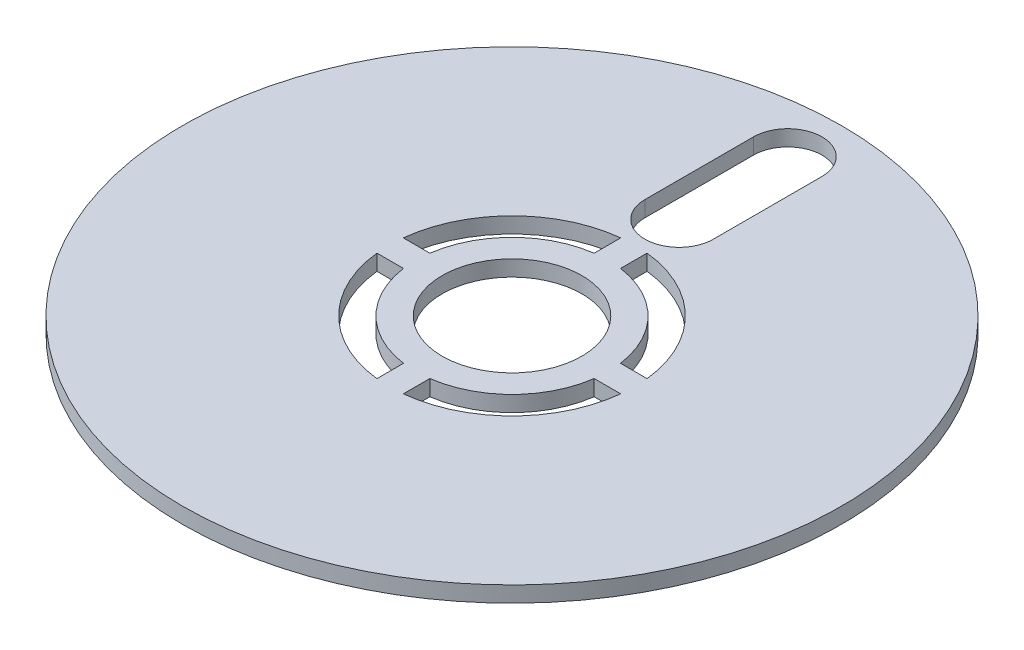
SolidWorks part; units mm, degrees
ref_plane "Front Plane" through (0, 0, 0) normal (0, 0, 1) x (1, 0, 0)
ref_plane "Top Plane" through (0, 0, 0) normal (0, 1, 0) x (1, 0, 0)
ref_plane "Right Plane" through (0, 0, 0) normal (1, 0, 0) x (0, 0, -1)
sketch "Sketch1" plane through (0, 0, 0) normal (0, 1, 0) x (1, 0, 0)
  line L0 (-2.5, 18.078) -> (-2.5, 23.1152)
  line L1 (2.5, 18.078) -> (2.5, 23.1152)
  line L2 (18.078, 2.5) -> (23.1152, 2.5)
  line L3 (18.078, -2.5) -> (23.1152, -2.5)
  line L4 (2.5, -18.078) -> (2.5, -23.1152)
  line L5 (-2.5, -18.078) -> (-2.5, -23.1152)
  line L6 (-18.078, -2.5) -> (-23.1152, -2.5)
  line L7 (-18.078, 2.5) -> (-23.1152, 2.5)
  circle A1 centre (0, 0) radius 13.25
  arc A2 (-2.5, 23.1152) -> (-23.1152, 2.5) centre (0, 0) ccw
  arc A3 (-2.5, 18.078) -> (-18.078, 2.5) centre (0, 0) ccw
  circle A4 centre (0, 0) radius 62.5
  arc A5 (18.078, 2.5) -> (2.5, 18.078) centre (0, 0) ccw
  arc A6 (23.1152, 2.5) -> (2.5, 23.1152) centre (0, 0) ccw
  arc A7 (2.5, -18.078) -> (18.078, -2.5) centre (0, 0) ccw
  arc A8 (2.5, -23.1152) -> (23.1152, -2.5) centre (0, 0) ccw
  arc A9 (-23.1152, -2.5) -> (-2.5, -23.1152) centre (0, 0) ccw
  arc A10 (-18.078, -2.5) -> (-2.5, -18.078) centre (0, 0) ccw
  point P25 (0, 0)
  point P94 (0, 0)
  dimension "D1" = 125
  dimension "D2" = 26.5
  dimension "D3" = 46.5
  dimension "D4" = 36.5
  dimension "D5" = 5
  dimension "D6" = 2.5
  dimension "D7" = 4
extrude "Boss-Extrude1" add sketch "Sketch1" along normal blind 3
sketch "Sketch3" plane through (0, 3, 0) normal (0, 1, 0) x (1, 0, 0)
  circle A0 centre (0, 0) radius 20.75
  point P4 (0, 0)
  dimension "D1" = 41.5
sketch "Sketch4" plane through (0, 3, 0) normal (0, 1, 0) x (1, 0, 0)
  line L0 (0, 31.7) -> (0, 52.3) construction
  line L1 (-6.5, 31.7) -> (-6.5, 52.3)
  line L2 (6.5, 31.7) -> (6.5, 52.3)
  arc A0 (-6.5, 31.7) -> (6.5, 31.7) centre (0, 31.7) ccw
  arc A1 (6.5, 52.3) -> (-6.5, 52.3) centre (0, 52.3) ccw
  point P3 (0, 42)
  dimension "D1" = 6.5
  dimension "D2" = 42
  dimension "D3" = 20.6
extrude "Cut-Extrude1" cut sketch "Sketch4" against normal through all
sketch "Sketch5" plane through (0, 3, 0) normal (0, 1, 0) x (1, 0, 0)
  circle A0 centre (0, 10) radius 32
  point P2 (0, 0)
  dimension "D1" = 64
  dimension "D2" = 10
